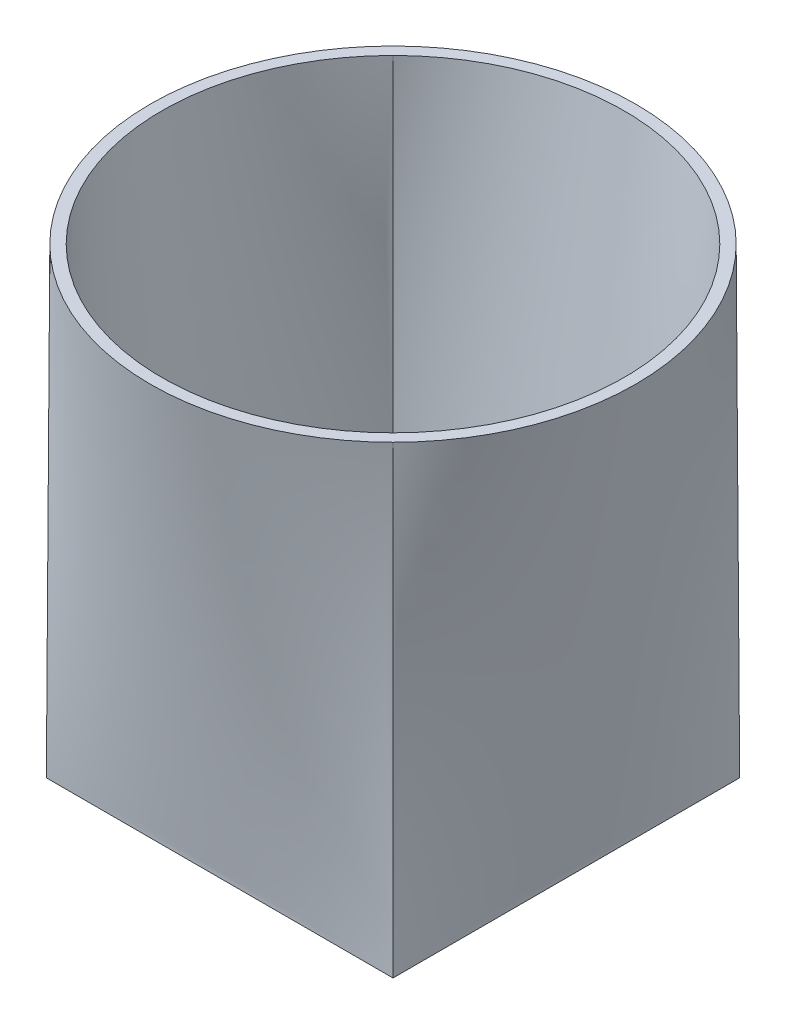
SolidWorks part; units mm, degrees
ref_plane "Front Plane" through (0, 0, 0) normal (0, 0, 1) x (1, 0, 0)
ref_plane "Top Plane" through (0, 0, 0) normal (0, 1, 0) x (1, 0, 0)
ref_plane "Right Plane" through (0, 0, 0) normal (1, 0, 0) x (0, 0, -1)
sketch "Sketch1" plane through (0, 0, 0) normal (0, 1, 0) x (1, 0, 0)
  line L1 (-75, 75) -> (75, 75)
  line L2 (-75, 75) -> (-75, -75)
  line L3 (-75, -75) -> (75, -75)
  line L4 (75, 75) -> (75, -75)
  line L5 (-75, 75) -> (75, -75) construction
  line L6 (-75, -75) -> (75, 75) construction
  point P0 (0, 0)
  dimension "D1" = 150
  dimension "D2" = 150
ref_plane "Plane1" through (0, 200, 0) normal (0, 1, 0) x (1, 0, 0)
sketch "Sketch2" plane through (0, 200, 0) normal (0, 1, 0) x (1, 0, 0)
  circle A0 centre (0, 0) radius 105
  dimension "D1" = 210
loft "Loft1" add profiles "Sketch2", "Sketch1"
sketch "Sketch3" plane through (0, 200, 0) normal (0, 1, 0) x (1, 0, 0)
  circle A0 centre (0, 0) radius 100
sketch "Sketch4" plane through (0, 0, 0) normal (0, -1, 0) x (1, 0, 0)
  line L1 (-72.5, 72.5) -> (72.5, 72.5)
  line L2 (-72.5, 72.5) -> (-72.5, -72.5)
  line L3 (-72.5, -72.5) -> (72.5, -72.5)
  line L4 (72.5, 72.5) -> (72.5, -72.5)
  line L5 (-72.5, 72.5) -> (72.5, -72.5) construction
  line L6 (-72.5, -72.5) -> (72.5, 72.5) construction
  point P1 (0, 0)
  dimension "D1" = 145
  dimension "D2" = 145
loft "Cut-Loft1" cut profiles "Sketch4", "Sketch3"
sketch "Sketch5" plane through (0, 200, 0) normal (0, 1, 0) x (1, 0, 0)
  circle A0 centre (0, 0) radius 10
  dimension "D1" = 20
